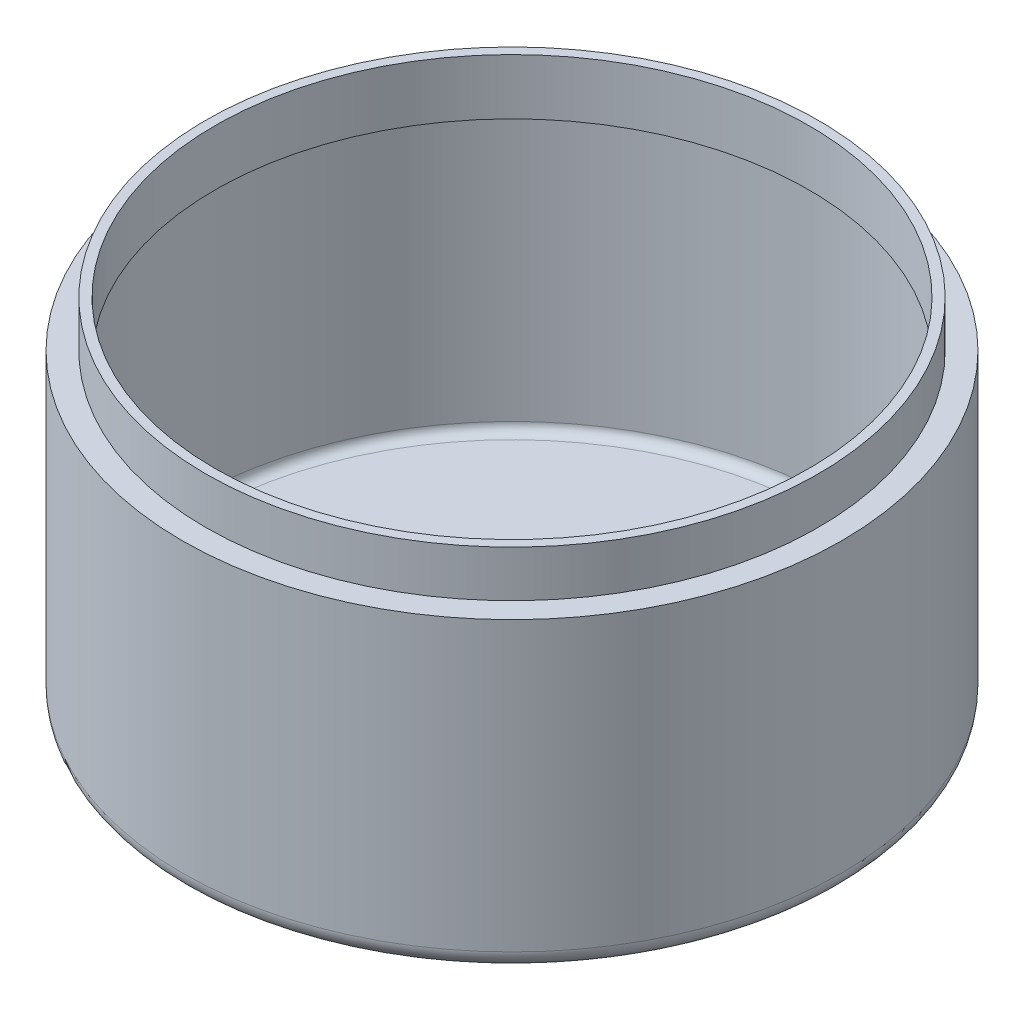
SolidWorks part; units mm, degrees
material "聚脂树脂"
ref_plane "前视基准面" through (0, 0, 0) normal (0, 0, 1) x (1, 0, 0)
ref_plane "上视基准面" through (0, 0, 0) normal (0, 1, 0) x (1, 0, 0)
ref_plane "右视基准面" through (0, 0, 0) normal (1, 0, 0) x (0, 0, -1)
other "Configuration Table"
ref_axis "基准轴1" through (0, 1.9, 0) along (0, -1, 0)
sketch "草图1" plane through (0, 0, 0) normal (1, 0, 0) x (0, 0, -1)
  line L0 (33, 0) -> (33, -5)
  line L2 (33, -5) -> (35.5, -5)
  line L6 (35.5, -5) -> (35.5, -36)
  line L7 (33.5, -38) -> (0, -38)
  line L23 (32, 0) -> (32, -6)
  line L24 (32, -6) -> (34.5, -6)
  line L25 (33, 0) -> (33, -5)
  line L26 (34.5, -6) -> (34.5, -36)
  line L27 (33.5, -37) -> (0, -37)
  line L28 (33, 0) -> (32, 0)
  line L29 (0, -38) -> (0, -37)
  arc A1 (35.5, -36) -> (33.5, -38) centre (33.5, -36) cw
  arc A11 (34.5, -36) -> (33.5, -37) centre (33.5, -36) cw
  point P21 (35.5, -5)
  dimension "D4" = 1
  dimension "D1" = 2
  dimension "D2" = 35.5
  dimension "D3" = 38
revolve "旋转1" add sketch "草图1" angle 360 about axis through (0, 1.9, 0) along (0, -1, 0)
